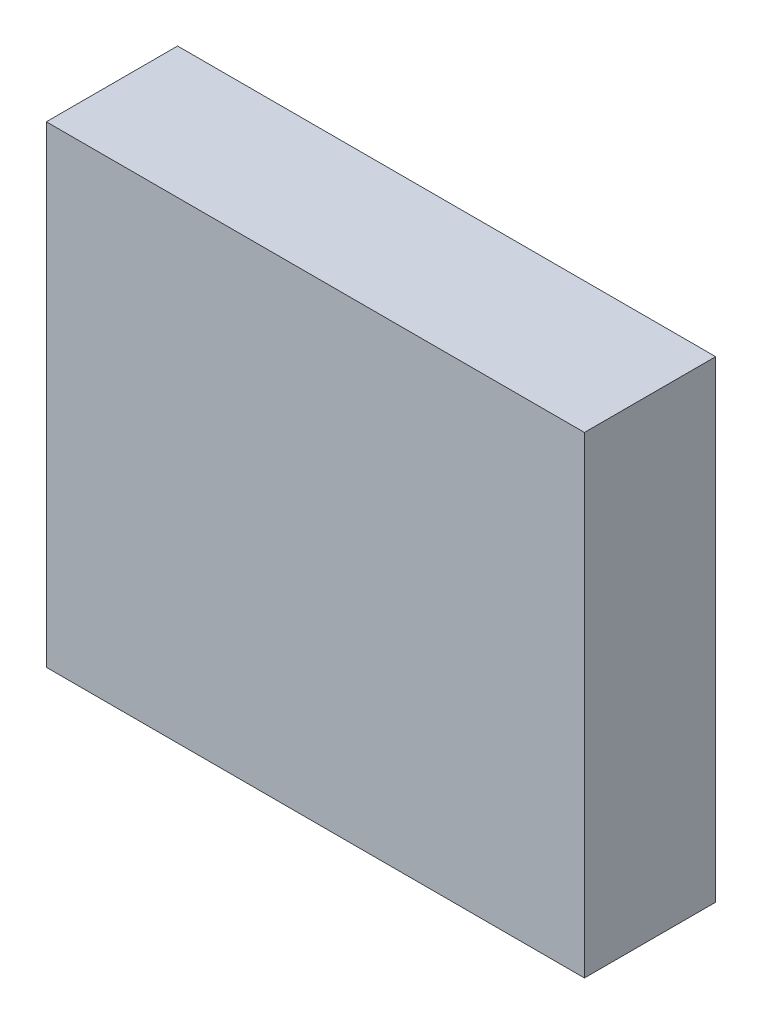
SolidWorks part; units mm, degrees
ref_plane "Front Plane" through (0, 0, 0) normal (0, 0, 1) x (1, 0, 0)
ref_plane "Top Plane" through (0, 0, 0) normal (0, 1, 0) x (1, 0, 0)
ref_plane "Right Plane" through (0, 0, 0) normal (1, 0, 0) x (0, 0, -1)
sketch "Sketch1" plane through (0, 0, 0) normal (0, 0, 1) x (1, 0, 0)
  line L0 (-2.25, 2) -> (1.85, 2)
  line L1 (1.85, 2) -> (1.85, -1.6)
  line L2 (1.85, -1.6) -> (-2.25, -1.6)
  line L3 (-2.25, -1.6) -> (-2.25, 2)
extrude "Component_Outline" add sketch "Sketch1" along normal blind 1 separate body
sketch3d "3DSketch1"
  line L0 (0, 0, 0) -> (1, 0, 0)
  line L1 (0, 0, 0) -> (0, 1, 0)
  line L2 (0, 0, 0) -> (0, 0, 1)
  point P0 (0, 0, 0)
